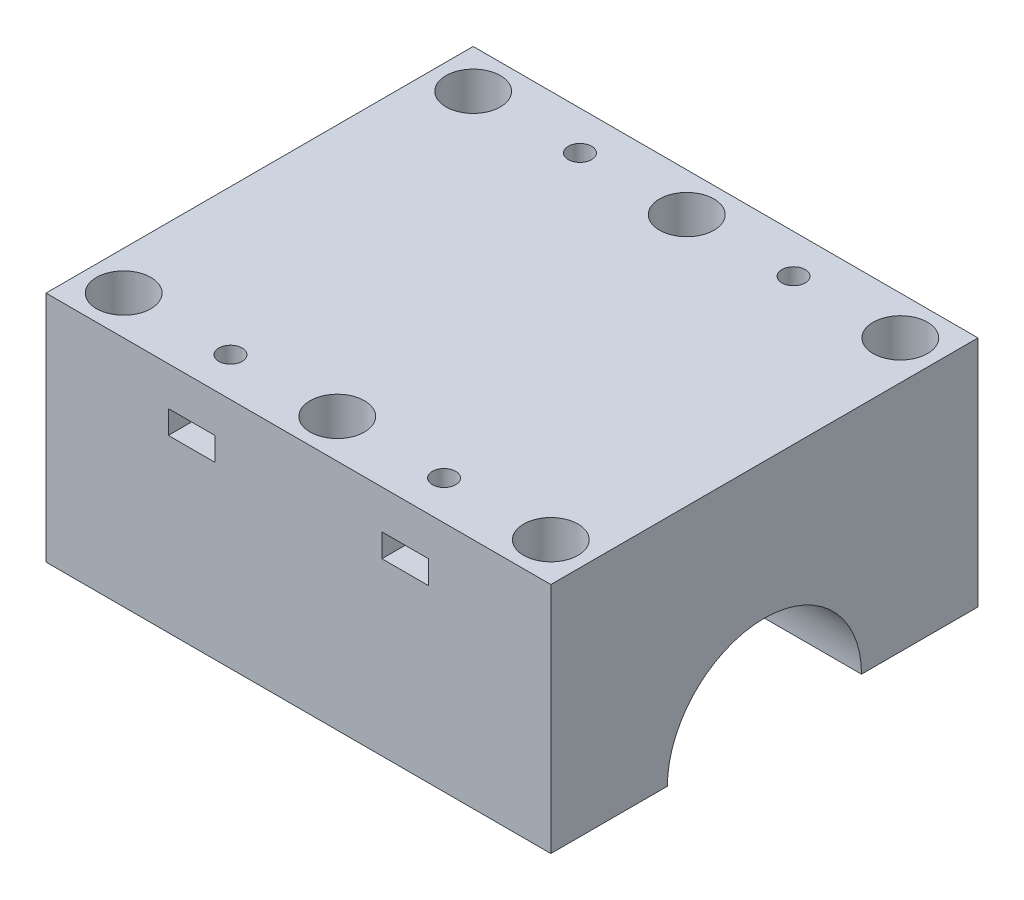
SolidWorks part; units mm, degrees
ref_plane "Alzado" through (0, 0, 0) normal (0, 0, 1) x (1, 0, 0)
ref_plane "Planta" through (0, 0, 0) normal (0, 1, 0) x (1, 0, 0)
ref_plane "Vista lateral" through (0, 0, 0) normal (1, 0, 0) x (0, 0, -1)
sketch "Croquis2" plane through (0, 0, 0) normal (0, 1, 0) x (1, 0, 0)
  line L4 (0, 0) -> (0, 55)
  line L5 (65, 55) -> (65, 0)
  line L6 (65, 55) -> (0, 55)
  line L8 (0, 0) -> (65, 0)
  circle A0 centre (5, 50) radius 1.5
  circle A1 centre (32.5, 50) radius 1.5
  circle A2 centre (60, 50) radius 1.5
  circle A3 centre (5, 5) radius 1.5
  circle A4 centre (32.5, 5) radius 1.5
  circle A5 centre (60, 5) radius 1.5
extrude "Saliente-Extruir1" add sketch "Croquis2" along normal blind 5
sketch "Croquis4" plane through (0, 5, 0) normal (0, 1, 0) x (1, 0, 0)
  line L17 (0, 0) -> (65, 0)
  line L18 (0, 0) -> (0, 55)
  line L19 (0, 55) -> (65, 55)
  line L20 (65, 0) -> (65, 55)
  circle A0 centre (5, 50) radius 3.5
  circle A1 centre (32.5, 50) radius 3.5
  circle A2 centre (60, 50) radius 3.5
  circle A3 centre (60, 5) radius 3.5
  circle A4 centre (32.5, 5) radius 3.5
  circle A5 centre (5, 5) radius 3.5
  dimension "D1" = 7
  dimension "D2" = 7
  dimension "D3" = 7
  dimension "D4" = 7
  dimension "D5" = 7
  dimension "D6" = 7
extrude "Saliente-Extruir2" add sketch "Croquis4" along normal blind 25
sketch "Croquis6" plane through (65, 0, 0) normal (1, 0, 0) x (0, 0, -1)
  line L0 (0, 0) -> (55, 0) construction
  line L1 (0, 30) -> (0, 0) construction
  circle A0 centre (27.5, 0) radius 12.5
  dimension "D1" = 25
  dimension "D2" = 27.5
extrude "Cortar-Extruir1" cut sketch "Croquis6" against normal offset from surface (60 mm away) 5 contours A0 up to face at (0, 15, -27.5)
sketch "Croquis7" plane through (0, 0, 0) normal (-1, 0, 0) x (0, 0, 1)
  line L0 (-55, 0) -> (0, 0) construction
  circle A0 centre (-27.5, 0) radius 6.5
  dimension "D1" = 13
extrude "Cortar-Extruir2" cut sketch "Croquis7" against normal blind 5 contours A0
sketch "Croquis8" plane through (0, 30, 0) normal (0, 1, 0) x (1, 0, 0)
  line L0 (0, 55) -> (0, 0) construction
  line L1 (65, 55) -> (0, 55) construction
  line L2 (65, 0) -> (65, 55) construction
  line L3 (0, 0) -> (65, 0) construction
  circle A0 centre (18.75, 50) radius 1.5
  circle A1 centre (46.25, 50) radius 1.5
  circle A2 centre (46.25, 5) radius 1.5
  circle A3 centre (18.75, 5) radius 1.5
  dimension "D1" = 18.75
  dimension "D2" = 3
  dimension "D3" = 3
  dimension "D4" = 3
  dimension "D5" = 3
  dimension "D6" = 5
  dimension "D7" = 5
  dimension "D8" = 18.75
  dimension "D9" = 18.75
  dimension "D10" = 5
  dimension "D11" = 5
  dimension "D12" = 18.75
extrude "Cortar-Extruir3" cut sketch "Croquis8" against normal blind 10
sketch "Croquis9" plane through (0, 0, 0) normal (0, 0, 1) x (1, 0, 0)
  line L2 (18.75, 30) -> (18.75, 0) construction
  line L15 (0, 30) -> (65, 30) construction
  line L16 (30.25, 0) -> (-30.25, 0) construction
  line L17 (0, 30) -> (0, 0) construction
  line L18 (15.75, 22) -> (21.75, 22)
  line L19 (15.75, 22) -> (15.75, 25)
  line L20 (15.75, 25) -> (21.75, 25)
  line L21 (21.75, 25) -> (21.75, 22)
  line L22 (32.5, 30) -> (32.5, 0) construction
  line L23 (49.25, 22) -> (49.25, 25)
  line L24 (49.25, 22) -> (43.25, 22)
  line L25 (43.25, 25) -> (43.25, 22)
  line L26 (49.25, 25) -> (43.25, 25)
  dimension "D1" = 18.75
  dimension "D2" = 8
  dimension "D3" = 3
  dimension "D4" = 6
  dimension "D5" = 3
extrude "Cortar-Extruir6" cut sketch "Croquis9" against normal blind 10
ref_plane "Plano1" through (0, 0, -27.5) normal (0, 0, 1) x (1, 0, 0)
mirror "Simetría1" about plane through (0, 0, -27.5) normal (0, 0, 1) of "Cortar-Extruir6"
